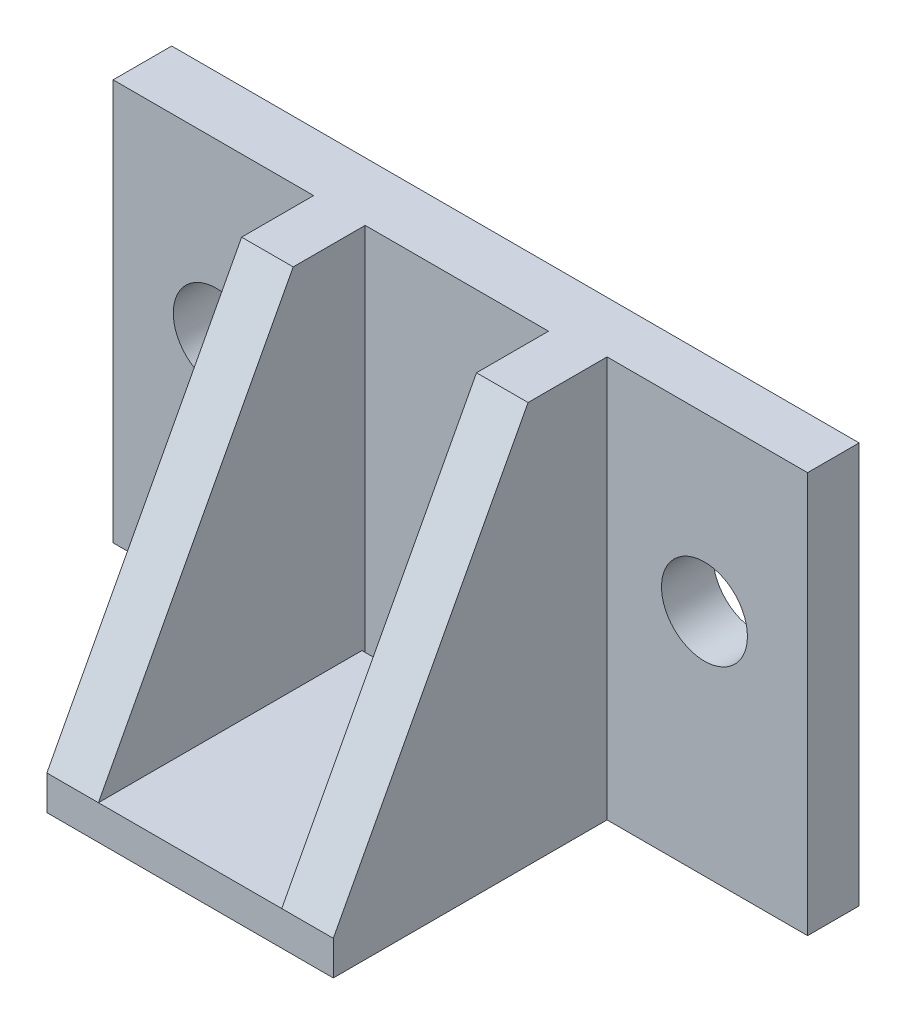
SolidWorks part; units mm, degrees
ref_plane "Front Plane" through (0, 0, 0) normal (0, 0, 1) x (1, 0, 0)
ref_plane "Top Plane" through (0, 0, 0) normal (0, 1, 0) x (1, 0, 0)
ref_plane "Right Plane" through (0, 0, 0) normal (1, 0, 0) x (0, 0, -1)
sketch "Sketch1" plane through (0, 0, 0) normal (0, 1, 0) x (1, 0, 0)
  line L0 (0, 0) -> (120, 0)
  line L1 (120, 0) -> (120, -9)
  line L2 (120, -9) -> (85, -9)
  line L3 (85, -9) -> (85, -22.7926)
  line L4 (85, -22.7926) -> (76, -22.7926)
  line L5 (76, -22.7926) -> (76, -10.2259)
  line L6 (76, -10.2259) -> (44, -10.2259)
  line L7 (44, -10.2259) -> (44, -22.7926)
  line L8 (44, -22.7926) -> (35, -22.7926)
  line L9 (35, -22.7926) -> (35, -10.2259)
  line L10 (35, -10.2259) -> (0, -10.2259)
  line L11 (0, -10.2259) -> (0, 0)
  dimension "D1" = 120
  dimension "D2" = 9
  dimension "D3" = 35
  dimension "D4" = 9
  dimension "D5" = 32
  dimension "D6" = 9
extrude "Boss-Extrude1" add sketch "Sketch1" along normal blind 70 contours L11 L0 L1 L2 L3 L4 L5 L6 L7 L8 L9 L10
sketch "Sketch2" plane through (0, 0, 9) normal (0, 0, 1) x (1, 0, 0)
  circle A0 centre (102, 40) radius 7.5
  dimension "D3" = 15
extrude "Cut-Extrude1" cut sketch "Sketch2" against normal blind 9
sketch "Sketch3" plane through (0, 0, 10.2259) normal (0, 0, 1) x (1, 0, 0)
  circle A0 centre (18, 40) radius 7.5
  dimension "D3" = 15
extrude "Cut-Extrude2" cut sketch "Sketch3" against normal blind 9
sketch "Sketch4" plane through (85, 0, 0) normal (1, 0, 0) x (0, 0, -1)
  line L0 (-56.7926, 0) -> (-22.7926, 0)
  line L1 (-56.7926, 0) -> (-56.7926, 6)
  line L2 (-56.7926, 6) -> (-22.7926, 70)
  line L3 (-22.7926, 0) -> (-22.7926, 70)
  dimension "D1" = 34
  dimension "D2" = 6
extrude "Boss-Extrude7" add sketch "Sketch4" against normal blind 9 contours L3 L2 L1 L0
sketch "Sketch7" plane through (35, 0, 0) normal (-1, 0, 0) x (0, 0, 1)
  line L0 (22.7926, 0) -> (56.7926, 0)
  line L1 (22.7926, 0) -> (10.2259, 0) construction
  line L2 (22.7926, 70) -> (22.7926, 0) construction
  line L3 (56.7926, 0) -> (56.7926, 6)
  line L4 (56.7926, 6) -> (22.7926, 70)
  line L5 (22.7926, 70) -> (22.7926, 0)
extrude "Boss-Extrude8" add sketch "Sketch7" against normal blind 9
sketch "Sketch8" plane through (0, 0, 56.7926) normal (0, 0, 1) x (1, 0, 0)
  line L1 (44, 6) -> (76, 6)
  line L2 (44, 6) -> (44, 0)
  line L3 (44, 0) -> (76, 0)
  line L4 (76, 6) -> (76, 0)
extrude "Boss-Extrude9" add sketch "Sketch8" against normal blind 46
sketch "Sketch10" plane through (0, 0, 1.2259) normal (0, 0, 1) x (1, 0, 0)
  circle A2 centre (18, 40) radius 7.5
extrude "Cut-Extrude3" cut sketch "Sketch10" against normal blind 46
